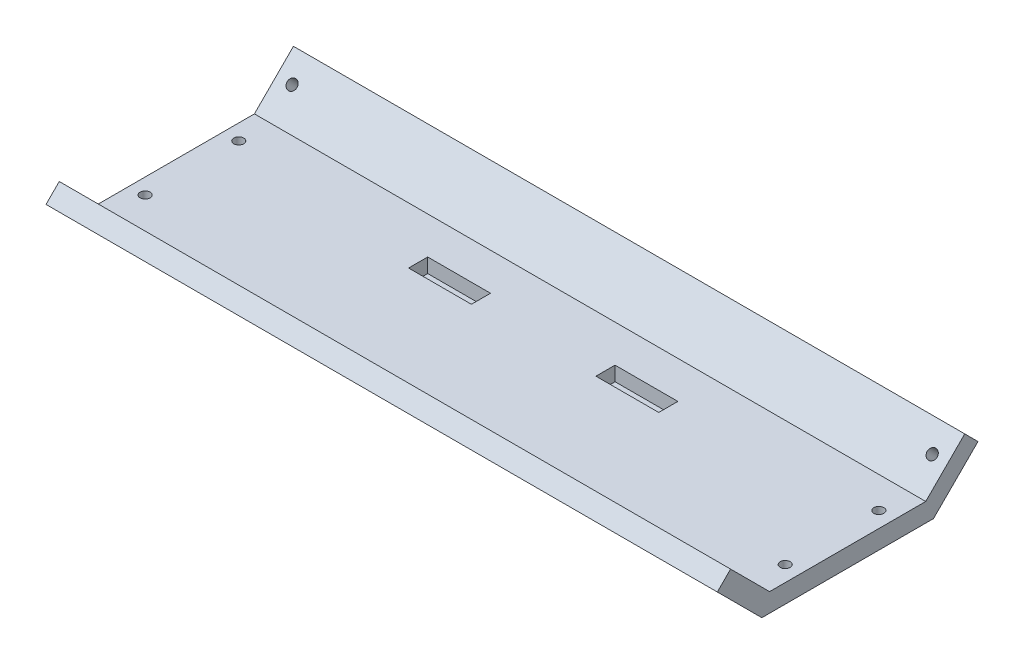
SolidWorks part; units mm, degrees
ref_plane "Front Plane" through (0, 0, 0) normal (0, 0, 1) x (1, 0, 0)
ref_plane "Top Plane" through (0, 0, 0) normal (0, 1, 0) x (1, 0, 0)
ref_plane "Right Plane" through (0, 0, 0) normal (1, 0, 0) x (0, 0, -1)
sketch "Sketch2" plane through (0, 0, 0) normal (1, 0, 0) x (0, 0, -1)
  line L0 (-25, 0) -> (25, 0)
  line L1 (25, 0) -> (37.5, 12.5)
  line L2 (-25, 0) -> (-37.5, 12.5)
  line L8 (27.4853, -6) -> (41.7426, 8.2574)
  line L9 (-27.4853, -6) -> (27.4853, -6)
  line L10 (-27.4853, -6) -> (-41.7426, 8.2574)
  line L11 (-37.5, 12.5) -> (-41.7426, 8.2574)
  line L12 (37.5, 12.5) -> (41.7426, 8.2574)
  line L13 (-37.5, 12.5) -> (-50, 25) construction
  line L14 (37.5, 12.5) -> (50, 25) construction
  point P4 (0, 0)
  dimension "D2" = 135
  dimension "D3" = 135
  dimension "D1" = 100
  dimension "D4" = 25
  dimension "D5" = 6
extrude "Main" add sketch "Sketch2" along normal mid plane 215
hole_wizard "Ø3.0mm Dowel Hole2" positions "3DSketch2" profile "Sketch4" hole size "Ø4.0" standard "ANSI Metric" end condition through all
sketch3d "3DSketch2"
  line L2 (107.5, 0, -25) -> (-107.5, 0, -25) construction
  line L3 (-102.5, 0, -25) -> (-102.5, 0, -15) construction
  line L4 (-102.5, 0, -15) -> (-102.5, 0, 15) construction
  line L5 (-102.5, 0, 15) -> (-102.5, 0, 25) construction
  line L6 (107.5, 0, 25) -> (-107.5, 0, 25) construction
  line L11 (102.5, 0, -25) -> (102.5, 0, -15) construction
  line L12 (102.5, 0, -15) -> (102.5, 0, 15) construction
  line L13 (102.5, 0, 15) -> (102.5, 0, 25) construction
  line L27 (102.5, 0, -25) -> (102.5, 7.0711, -32.0711) construction
  line L29 (102.5, 0, 25) -> (102.5, 7.0711, 32.0711) construction
  line L31 (-102.5, 7.0711, 32.0711) -> (-102.5, 0, 25) construction
  line L35 (-102.5, 7.0711, -32.0711) -> (-107.5, 7.0711, -32.0711) construction
  line L36 (-107.5, 12.5, -37.5) -> (-107.5, 0, -25) construction
  line L38 (-102.5, 7.0711, 32.0711) -> (-107.5, 7.0711, 32.0711) construction
  line L39 (-107.5, 0, 25) -> (-107.5, 12.5, 37.5) construction
  line L41 (102.5, 7.0711, -32.0711) -> (107.5, 7.0711, -32.0711) construction
  line L42 (107.5, 12.5, -37.5) -> (107.5, 0, -25) construction
  line L44 (102.5, 7.0711, 32.0711) -> (107.5, 7.0711, 32.0711) construction
  line L45 (107.5, 0, 25) -> (107.5, 12.5, 37.5) construction
  line L47 (102.5, 0, 25) -> (107.5, 0, 25) construction
  line L49 (-102.5, 0, 25) -> (-107.5, 0, 25) construction
  line L51 (-102.5, 7.0711, -32.0711) -> (-102.5, 0, -25) construction
  point P0 (-102.5, 7.0711, -32.0711)
  point P2 (-102.5, 0, -15)
  point P4 (-102.5, 0, 15)
  point P6 (-102.5, 7.0711, 32.0711)
  point P8 (102.5, 7.0711, 32.0711)
  point P10 (102.5, 0, 15)
  point P12 (102.5, 0, -15)
  point P14 (102.5, 7.0711, -32.0711)
  dimension "D1" = 5
  dimension "D2" = 10
  dimension "D3" = 10
sketch "Sketch4" plane through (-102.5, 7.0711, -32.0711) normal (1, 0, 0) x (0, -0.7071, 0.7071)
  line L0 (0, 0) -> (0, 16.0815)
  line L1 (0, 16.0815) -> (1.6, 16.0815)
  line L2 (1.6, 16.0815) -> (1.6, 0)
  line L5 (1.6, 0) -> (0, 0)
  line L11 (0, -6.35) -> (0, 107.95) construction
  dimension "Thru Hole Dia." = 3.2
  dimension "Thru Hole Depth" = 16.0815
sketch "Sketch5" plane through (0, 0, 0) normal (0, 1, 0) x (1, 0, 0)
  line L0 (0, 0) -> (-50, 0) construction
  line L1 (-73.25, 11.775) -> (-26.75, 11.775) construction
  line L2 (-73.25, 11.775) -> (-73.25, -11.775) construction
  line L3 (-73.25, -11.775) -> (-26.75, -11.775) construction
  line L4 (-26.75, 11.775) -> (-26.75, -11.775) construction
  line L5 (-73.25, 11.775) -> (-26.75, -11.775) construction
  line L6 (-73.25, -11.775) -> (-26.75, 11.775) construction
  circle A0 centre (-73.25, 11.775) radius 4
  circle A1 centre (-26.75, 11.775) radius 4
  circle A2 centre (-26.75, -11.775) radius 4
  circle A3 centre (-73.25, -11.775) radius 4
  circle A4 centre (-73.25, 11.775) radius 2.05
  circle A5 centre (-26.75, 11.775) radius 2.05
  circle A6 centre (-26.75, -11.775) radius 2.05
  circle A7 centre (-73.25, -11.775) radius 2.05
  point P0 (-50, 0)
  dimension "D1" = 8
  dimension "D2" = 4.1
  dimension "D3" = 46.5
  dimension "D4" = 23.55
  dimension "D5" = 50
extrude "ESP32 pegs" [suppressed] add sketch "Sketch5" along normal blind 5.7
sketch "Sketch6" plane through (0, 0, 0) normal (0, 1, 0) x (1, 0, 0)
  line L0 (0, 0) -> (0, 10) construction
  line L1 (19.9375, 13.0625) -> (40.0625, 13.0625)
  line L2 (19.9375, 13.0625) -> (19.9375, 6.9375)
  line L3 (19.9375, 6.9375) -> (40.0625, 6.9375)
  line L4 (40.0625, 13.0625) -> (40.0625, 6.9375)
  line L5 (19.9375, 13.0625) -> (40.0625, 6.9375) construction
  line L6 (19.9375, 6.9375) -> (40.0625, 13.0625) construction
  line L7 (30, 10) -> (0, 10) construction
  line L8 (-40.0625, 13.0625) -> (-19.9375, 13.0625)
  line L9 (-40.0625, 13.0625) -> (-40.0625, 6.9375)
  line L10 (-40.0625, 6.9375) -> (-19.9375, 6.9375)
  line L11 (-19.9375, 13.0625) -> (-19.9375, 6.9375)
  line L12 (-40.0625, 13.0625) -> (-19.9375, 6.9375) construction
  line L13 (-40.0625, 6.9375) -> (-19.9375, 13.0625) construction
  line L14 (0, 10) -> (-30, 10) construction
  point P0 (30, 10)
  point P5 (-30, 10)
  dimension "D1" = 80.125
  dimension "D2" = 6.125
  dimension "D3" = 39.875
  dimension "D4" = 10
extrude "Shelf cut" cut sketch "Sketch6" against normal through all
sketch "Sketch7" plane through (0, -6, 0) normal (0, -1, 0) x (1, 0, 0)
  line L1 (40.0625, -13.0625) -> (19.9375, -13.0625)
  line L2 (40.0625, -13.0625) -> (40.0625, -6.9375)
  line L3 (40.0625, -6.9375) -> (19.9375, -6.9375)
  line L4 (19.9375, -13.0625) -> (19.9375, -6.9375)
  line L5 (-19.9375, -13.0625) -> (-40.0625, -13.0625)
  line L6 (-19.9375, -13.0625) -> (-19.9375, -6.9375)
  line L7 (-19.9375, -6.9375) -> (-40.0625, -6.9375)
  line L8 (-40.0625, -13.0625) -> (-40.0625, -6.9375)
extrude "Boss-Extrude1" add sketch "Sketch7" against normal blind 1.4
equation "\"D1@Main\" = \"length\""
equation "\"D5@Sketch2\"=\"skin_th\""
equation "\"D1@Sketch2\"=\"height\""
equation "\"length\" = 215mm"
equation "\"width\" = 220mm"
equation "\"height\" = 100mm"
equation "\"skin_th\" = 6mm"
equation "\"shelf_height\" = 10mm"
equation "\"D4@Sketch6\"=\"shelf_height\""
